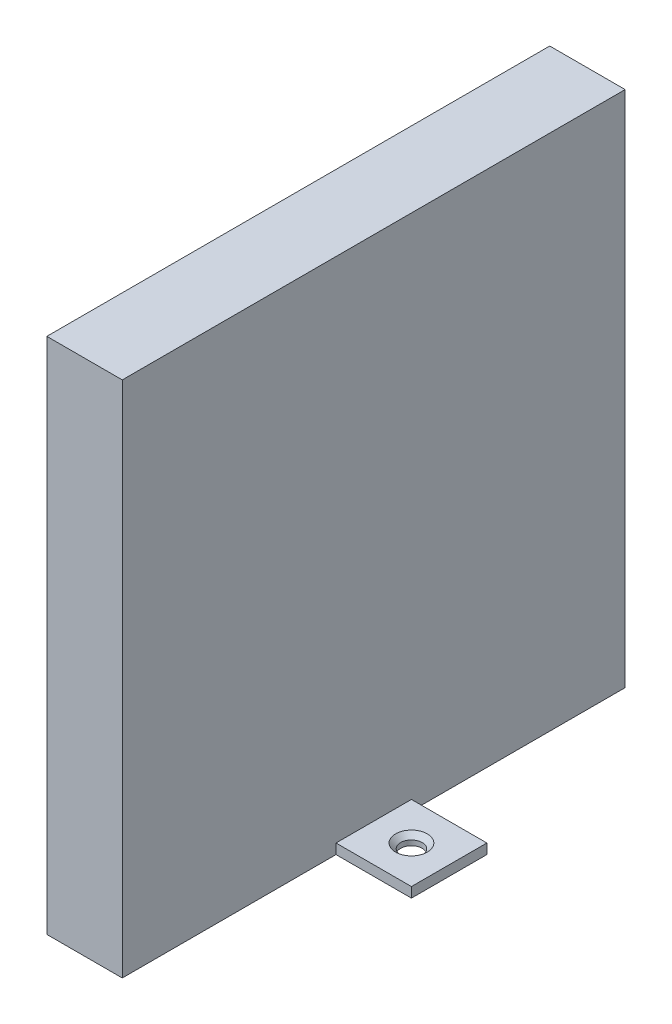
SolidWorks part; units mm, degrees
ref_plane "Front Plane" through (0, 0, 0) normal (0, 0, 1) x (1, 0, 0)
ref_plane "Top Plane" through (0, 0, 0) normal (0, 1, 0) x (1, 0, 0)
ref_plane "Right Plane" through (0, 0, 0) normal (1, 0, 0) x (0, 0, -1)
sketch "Sketch1" plane through (0, 0, 0) normal (0, 1, 0) x (1, 0, 0)
  line L0 (0, 0) -> (15, 0)
  line L1 (15, 0) -> (15, 100)
  line L2 (15, 100) -> (0, 100)
  line L3 (0, 100) -> (0, 0)
  dimension "D1" = 100
  dimension "D2" = 15
extrude "Boss-Extrude1" add sketch "Sketch1" along normal blind 103
sketch "Sketch2" plane through (0, 0, 0) normal (-1, 0, 0) x (0, 0, 1)
  line L0 (-57.5, 0) -> (-57.5, 2)
  line L1 (-100, 0) -> (0, 0) construction
  line L2 (-57.5, 2) -> (-42.5, 2)
  line L3 (-42.5, 2) -> (-42.5, 0)
  line L4 (-42.5, 0) -> (-57.5, 0)
  line L5 (-100, 103) -> (-100, 0) construction
  dimension "D1" = 15
  dimension "D2" = 2
  dimension "D3" = 42.5
extrude "Boss-Extrude2" add sketch "Sketch2" along normal blind 15
sketch "Sketch3" plane through (15, 0, 0) normal (1, 0, 0) x (0, 0, -1)
  line L0 (42.5, 0) -> (42.5, 2)
  line L1 (0, 0) -> (100, 0) construction
  line L2 (42.5, 2) -> (57.5, 2)
  line L3 (57.5, 2) -> (57.5, 0)
  line L4 (42.5, 0) -> (57.5, 0)
  line L5 (0, 103) -> (0, 0) construction
  dimension "D1" = 15
  dimension "D2" = 42.5
  dimension "D3" = 2
extrude "Boss-Extrude3" add sketch "Sketch3" along normal blind 15
sketch "Sketch4" plane through (0, 2, 0) normal (0, 1, 0) x (1, 0, 0)
  line L0 (30, 57.5) -> (15, 57.5) construction
  line L1 (30, 57.5) -> (30, 42.5) construction
  line L2 (-15, 57.5) -> (0, 57.5) construction
  line L3 (-15, 42.5) -> (-15, 57.5) construction
  circle A0 centre (-7.5, 50) radius 2.15
  circle A1 centre (22.5, 50) radius 2.15
  dimension "D1" = 4.3
  dimension "D2" = 4.3
  dimension "D3" = 7.5
  dimension "D4" = 7.5
  dimension "D5" = 7.5
  dimension "D6" = 7.5
extrude "Cut-Extrude1" cut sketch "Sketch4" against normal blind 15
chamfer "Chamfer1" distance 1 angle 45 2 edges at (22.5, 2, -47.85) (-7.5, 2, -47.85)
